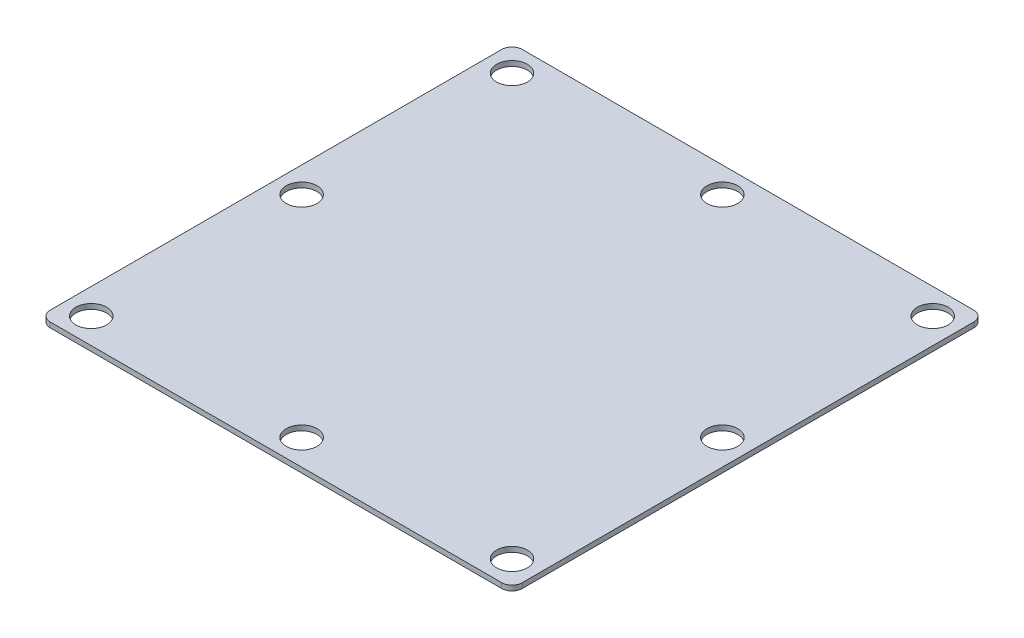
SolidWorks part; units mm, degrees
material "Rubber"
ref_plane "Front Plane" through (0, 0, 0) normal (0, 0, 1) x (1, 0, 0)
ref_plane "Top Plane" through (0, 0, 0) normal (0, 1, 0) x (1, 0, 0)
ref_plane "Right Plane" through (0, 0, 0) normal (1, 0, 0) x (0, 0, -1)
sketch "Sketch1" plane through (0, 0, 0) normal (0, 1, 0) x (1, 0, 0)
  line L1 (-46, -46) -> (46, -46)
  line L2 (-46, -46) -> (-46, 46)
  line L3 (-46, 46) -> (46, 46)
  line L4 (46, -46) -> (46, 46)
  line L5 (-46, -46) -> (46, 46) construction
  line L6 (-46, 46) -> (46, -46) construction
  point P0 (0, 0)
  dimension "D1" = 92
extrude "Boss-Extrude1" add sketch "Sketch1" along normal mid plane 1
fillet "Fillet1" radius 2 4 edges at (46, 0, 46) (-46, 0, -46) (46, 0, -46) (-46, 0, 46)
sketch "Sketch2" plane through (0, 0.5, 0) normal (0, 1, 0) x (1, 0, 0)
  line L0 (46, -44) -> (46, 44) construction
  line L1 (-41, -41) -> (41, -41) construction
  line L2 (-41, -41) -> (-41, 41) construction
  line L3 (-41, 41) -> (41, 41) construction
  line L4 (41, -41) -> (41, 41) construction
  line L5 (-41, -41) -> (41, 41) construction
  line L6 (-41, 41) -> (41, -41) construction
  line L7 (0, 0) -> (0, 41) construction
  line L8 (0, 0) -> (41, 0) construction
  line L9 (0, 0) -> (-41, 0) construction
  line L10 (0, 0) -> (0, -41) construction
  circle A0 centre (-41, 41) radius 3
  circle A1 centre (0, 41) radius 3
  circle A2 centre (41, 41) radius 3
  circle A3 centre (41, 0) radius 3
  circle A4 centre (41, -41) radius 3
  circle A5 centre (0, -41) radius 3
  circle A6 centre (-41, -41) radius 3
  circle A7 centre (-41, 0) radius 3
  point P0 (0, 0)
  dimension "D2" = 6
  dimension "D1" = 5
extrude "Cut-Extrude1" cut sketch "Sketch2" against normal through all both and the other way through all
